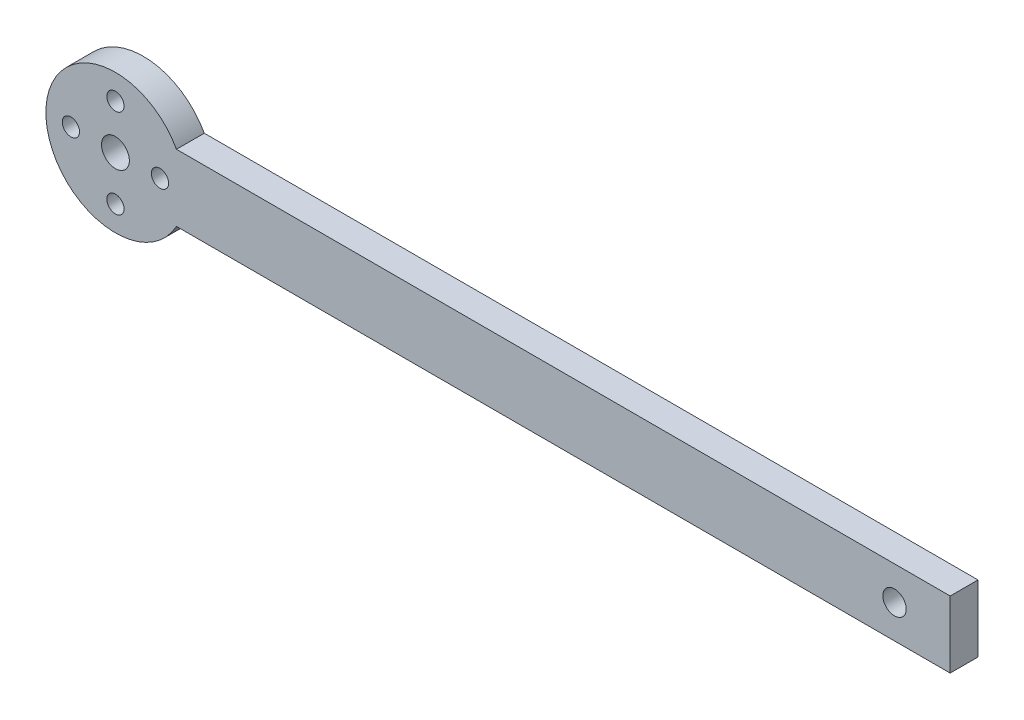
SolidWorks part; units mm, degrees
ref_plane "Front Plane" through (0, 0, 0) normal (0, 0, 1) x (1, 0, 0)
ref_plane "Top Plane" through (0, 0, 0) normal (0, 1, 0) x (1, 0, 0)
ref_plane "Right Plane" through (0, 0, 0) normal (1, 0, 0) x (0, 0, -1)
sketch "Sketch1" plane through (0, 0, 0) normal (0, 0, 1) x (1, 0, 0)
  line L0 (10.9659, 6) -> (150, 6)
  line L1 (150, 6) -> (150, -6)
  line L2 (150, -6) -> (10.9659, -6)
  arc A0 (10.9659, 6) -> (10.9659, -6) centre (0, 0) ccw
  dimension "D1" = 25
  dimension "D2" = 150
  dimension "D3" = 6
extrude "Boss-Extrude1" add sketch "Sketch1" along normal blind 5
sketch "Sketch2" plane through (0, 0, 5) normal (0, 0, 1) x (1, 0, 0)
  line L0 (150, -6) -> (150, 6) construction
  circle A0 centre (140, 0) radius 2.1
  circle A1 centre (0, 0) radius 2.5
  circle A2 centre (0, 8) radius 1.55
  circle A3 centre (8, 0) radius 1.55
  circle A4 centre (0, -8) radius 1.55
  circle A5 centre (-8, 0) radius 1.55
  dimension "D1" = 4.2
  dimension "D3" = 5
  dimension "D4" = 3.1
  dimension "D2" = 10
  dimension "D5" = 8
  dimension "D6" = 8
  dimension "D7" = 8
  dimension "D8" = 8
extrude "Cut-Extrude1" cut sketch "Sketch2" against normal through all
